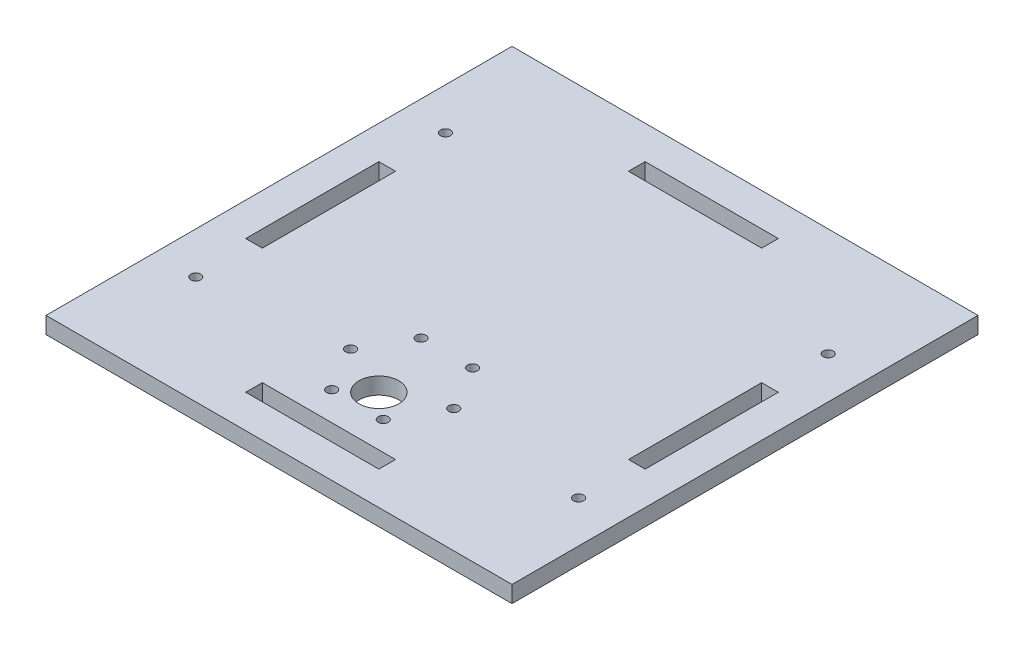
SolidWorks part; units mm, degrees
material "CA"
ref_plane "Alzado" through (0, 0, 0) normal (0, 0, 1) x (1, 0, 0)
ref_plane "Planta" through (0, 0, 0) normal (0, 1, 0) x (1, 0, 0)
ref_plane "Vista lateral" through (0, 0, 0) normal (1, 0, 0) x (0, 0, -1)
sketch "Croquis2" plane through (0, 0, 0) normal (0, 1, 0) x (1, 0, 0)
  line L0 (0, 0) -> (140, 0)
  line L1 (140, 0) -> (140, 140)
  line L2 (140, 140) -> (0, 140)
  line L3 (0, 140) -> (0, 0)
  line L4 (0, 0) -> (-1.0309, -0.8169)
  line L6 (50, 130) -> (90, 130)
  line L7 (90, 130) -> (90, 125)
  line L8 (90, 125) -> (50, 125)
  line L9 (50, 125) -> (50, 130)
  line L10 (50, 15) -> (50, 10)
  line L11 (90, 10) -> (90, 15)
  line L12 (50, 10) -> (90, 10)
  line L13 (90, 15) -> (50, 15)
  line L14 (125, 50) -> (130, 50)
  line L15 (130, 50) -> (130, 90)
  line L16 (130, 90) -> (125, 90)
  line L17 (125, 90) -> (125, 50)
  line L19 (15, 50) -> (10, 50)
  line L20 (10, 90) -> (15, 90)
  line L21 (15, 90) -> (15, 50)
  line L22 (10, 50) -> (10, 90)
  circle A0 centre (12.5, 107.5) radius 1.5
  circle A1 centre (12.5, 32.5) radius 1.5
  circle A6 centre (127.5, 32.5) radius 1.5
  circle A7 centre (127.5, 107.5) radius 1.5
  circle A8 centre (85.5, 37) radius 1.5
  circle A9 centre (77.75, 23.5766) radius 1.5
  circle A10 centre (62.25, 23.5766) radius 1.5
  circle A11 centre (54.5, 37) radius 1.5
  circle A12 centre (62.25, 50.4234) radius 1.5
  circle A13 centre (77.75, 50.4234) radius 1.5
  circle A14 centre (70, 30) radius 6
  point P17 (70, 140)
  point P18 (70, 0)
  point P19 (70, 10)
  point P20 (130, 70)
  point P23 (140, 70)
  point P60 (70, 37)
  dimension "D13" = 3
  dimension "D14" = 3
  dimension "D12" = 12
  dimension "D1" = 140
  dimension "D2" = 140
  dimension "D3" = 40
  dimension "D4" = 5
  dimension "D5" = 50
  dimension "D7" = 10
  dimension "D8" = 10
  dimension "D9" = 5
  dimension "D10" = 40
  dimension "D11" = 10
  dimension "D15" = 6
extrude "Saliente-Extruir1" add sketch "Croquis2" along normal blind 5 contours A0 | A6
